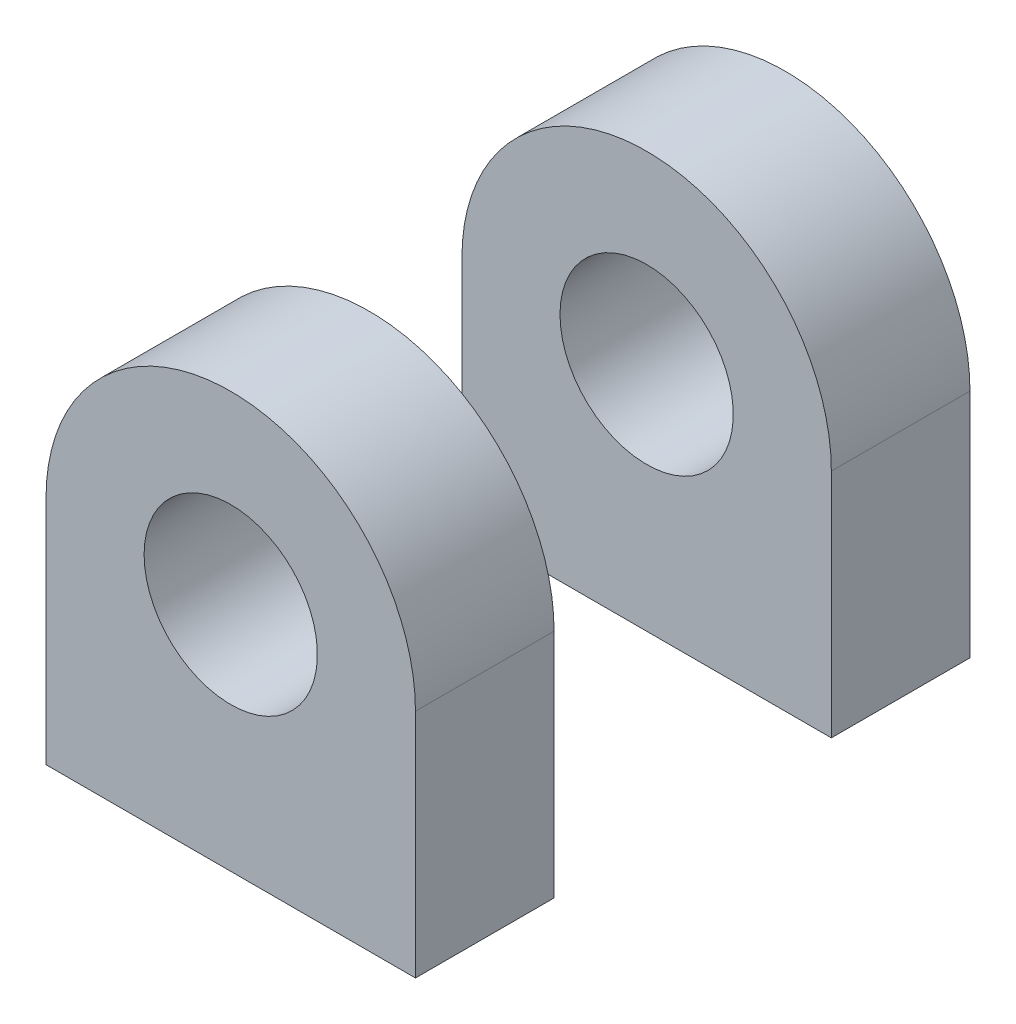
SolidWorks part; units mm, degrees
ref_plane "Front Plane" through (0, 0, 0) normal (0, 0, 1) x (1, 0, 0)
ref_plane "Top Plane" through (0, 0, 0) normal (0, 1, 0) x (1, 0, 0)
ref_plane "Right Plane" through (0, 0, 0) normal (1, 0, 0) x (0, 0, -1)
sketch "Sketch1" plane through (0, 0, 0) normal (0, 0, 1) x (1, 0, 0)
  line L1 (0, 0) -> (10.1533, 0)
  line L2 (0, 0) -> (0, 6.35)
  line L4 (10.1533, 0) -> (10.1533, 6.35)
  arc A0 (0, 6.35) -> (10.1533, 6.35) centre (5.0767, 6.35) cw
  circle A1 centre (5.0767, 6.35) radius 2.3813
  dimension "D1" = 4.7625
  dimension "D3" = 5.0767
  dimension "D2" = 6.35
extrude "Boss-Extrude1" add sketch "Sketch1" along normal mid plane 15.24 contours A0 L2 L1 L4 A1
sketch "Sketch2" plane through (0, 0, 0) normal (-1, 0, 0) x (0, 0, 1)
  line L0 (-7.62, 0) -> (-7.62, 6.35) construction
  line L1 (-3.81, 0) -> (3.81, 0)
  line L2 (-3.81, 0) -> (-3.81, 24.1712)
  line L3 (-3.81, 24.1712) -> (3.81, 24.1712)
  line L4 (3.81, 0) -> (3.81, 24.1712)
  line L5 (7.62, 0) -> (7.62, 6.35) construction
  line L6 (7.62, 0) -> (-7.62, 0) construction
  dimension "D1" = 3.81
  dimension "D2" = 3.81
  dimension "D3" = 0
  dimension "D4" = 24.1712
extrude "Cut-Extrude1" cut sketch "Sketch2" against normal blind 25.4 contours L2 L1 L4 L3
ref_plane "Plane1" through (5.0767, 0, 0) normal (-1, 0, 0) x (0, 0, 1)
